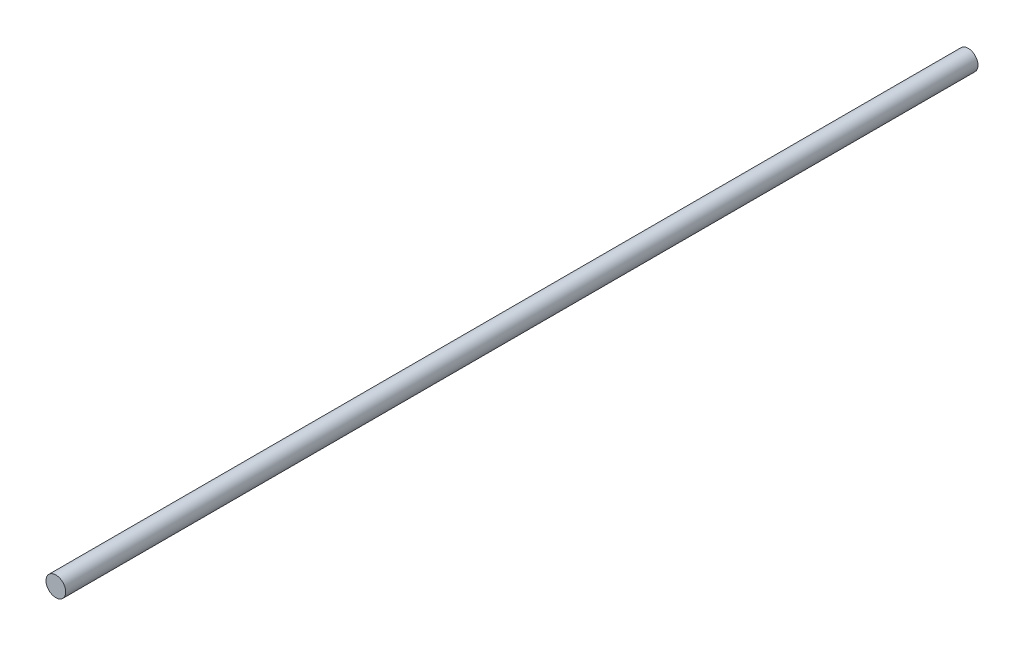
SolidWorks part; units mm, degrees
ref_plane "Front Plane" through (0, 0, 0) normal (0, 0, 1) x (1, 0, 0)
ref_plane "Top Plane" through (0, 0, 0) normal (0, 1, 0) x (1, 0, 0)
ref_plane "Right Plane" through (0, 0, 0) normal (1, 0, 0) x (0, 0, -1)
sketch "Sketch1" plane through (0, 0, 0) normal (0, 0, 1) x (1, 0, 0)
  circle A0 centre (0, 0) radius 2
  dimension "D1" = 4
extrude "Boss-Extrude1" add sketch "Sketch1" along normal blind 185
